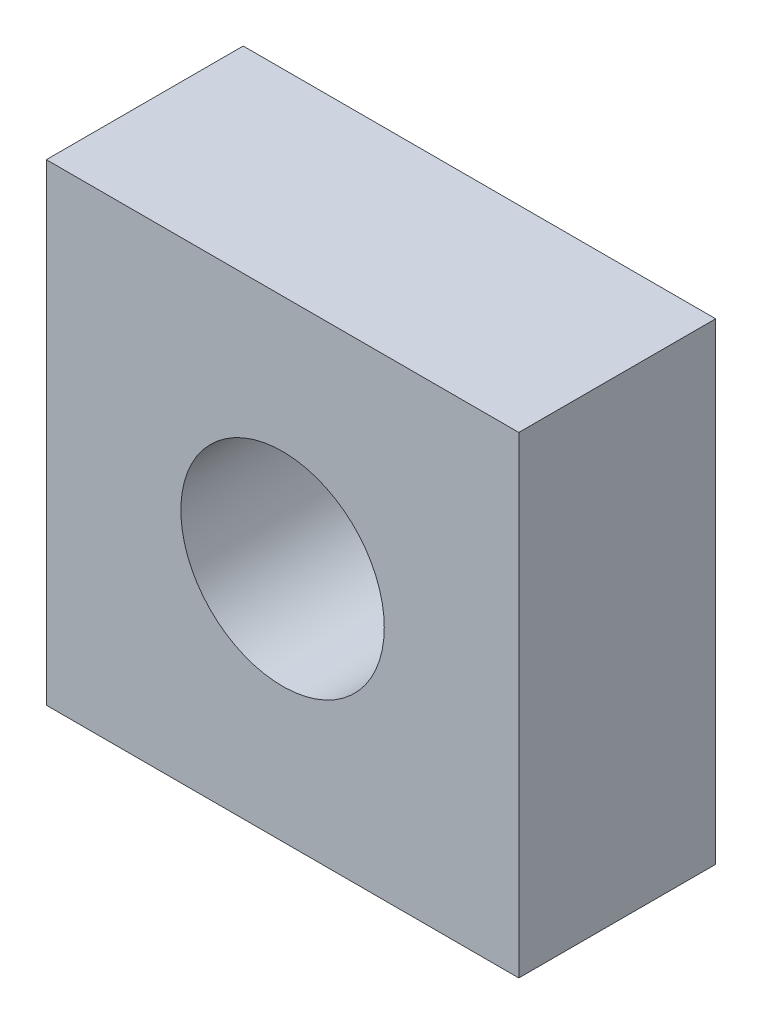
SolidWorks part; units mm, degrees
ref_plane "정면" through (0, 0, 0) normal (0, 0, 1) x (1, 0, 0)
ref_plane "윗면" through (0, 0, 0) normal (0, 1, 0) x (1, 0, 0)
ref_plane "우측면" through (0, 0, 0) normal (1, 0, 0) x (0, 0, -1)
sketch "Sketch1" plane through (0, 0, 0) normal (0, 0, 1) x (1, 0, 0)
  line L0 (-3.6, 3.6) -> (3.6, -3.6) construction
  line L1 (-3.6, 3.6) -> (3.6, 3.6)
  line L2 (-3.6, 3.6) -> (-3.6, -3.6)
  line L3 (-3.6, -3.6) -> (3.6, -3.6)
  line L4 (3.6, 3.6) -> (3.6, -3.6)
  point P4 (0, 0)
  dimension "D1" = 7.2
  dimension "D2" = 7.2
extrude "Boss-Extrude1" add sketch "Sketch1" along normal blind 3
sketch "Sketch2" plane through (0, 0, 3) normal (0, 0, 1) x (1, 0, 0)
  circle A0 centre (0, 0) radius 1.55
  dimension "D1" = 3.1
extrude "Cut-Extrude1" cut sketch "Sketch2" against normal blind 3 contours A0
